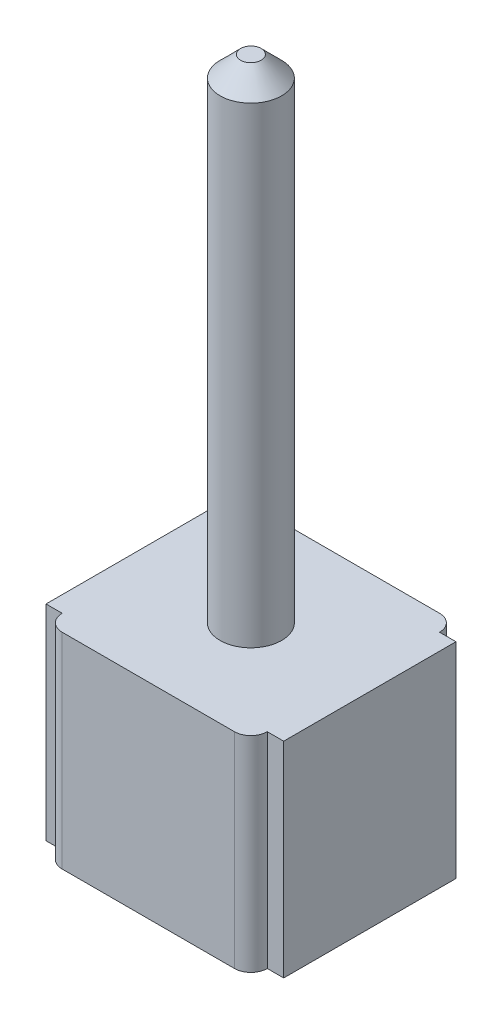
SolidWorks part; units mm, degrees
ref_plane "Plan de face" through (0, 0, 0) normal (0, 0, 1) x (1, 0, 0)
ref_plane "Plan de dessus" through (0, 0, 0) normal (0, 1, 0) x (1, 0, 0)
ref_plane "Plan de droite" through (0, 0, 0) normal (1, 0, 0) x (0, 0, -1)
sketch "Esquisse1" plane through (0, 0, 0) normal (0, 1, 0) x (1, 0, 0)
  line L0 (-1.25, 1.05) -> (-1.4469, 1.05)
  line L1 (-1.05, -1.25) -> (1.05, -1.25)
  line L3 (-1.05, 1.25) -> (1.05, 1.25)
  line L5 (-1.25, -1.25) -> (1.25, 1.25) construction
  line L6 (-1.25, 1.25) -> (1.25, -1.25) construction
  line L7 (-1.4469, 1.05) -> (-1.4469, -1.05)
  line L8 (-1.4469, -1.05) -> (-1.25, -1.05)
  line L10 (1.25, 1.05) -> (1.45, 1.05)
  line L11 (1.45, 1.05) -> (1.45, -1.05)
  line L12 (1.45, -1.05) -> (1.25, -1.05)
  arc A0 (-1.25, 1.05) -> (-1.05, 1.25) centre (-1.05, 1.05) cw
  arc A1 (-1.05, -1.25) -> (-1.25, -1.05) centre (-1.05, -1.05) cw
  arc A2 (1.05, -1.25) -> (1.25, -1.05) centre (1.05, -1.05) ccw
  arc A3 (1.05, 1.25) -> (1.25, 1.05) centre (1.05, 1.05) cw
  point P0 (0, 0)
  point P23 (0, 0)
  point P24 (0, 0)
  dimension "D3" = 0.2
  dimension "D1" = 2.5
  dimension "D2" = 2.5
extrude "Boss.-Extru.1" add sketch "Esquisse1" along normal blind 2.5
sketch "Esquisse3" plane through (0, 2.5, 0) normal (0, 1, 0) x (1, 0, 0)
  circle A0 centre (0, 0) radius 0.375
extrude "Boss.-Extru.2" add sketch "Esquisse3" along normal blind 6
chamfer "Chanfrein1" distance 0.25 angle 45 1 edges at (0, 8.5, 0.375)
sketch "Esquisse4" plane through (0, 0, 0) normal (0, -1, 0) x (1, 0, 0)
  line L1 (0, 0) -> (0.3042, 0)
  line L3 (0, -2.2509) -> (0.3042, -2.2509)
  line L4 (0.3042, 0) -> (0.3042, -2.2509)
  line L5 (0, 0) -> (-0.2993, 0)
  line L7 (0, -2.2509) -> (-0.2993, -2.2509)
  line L8 (-0.2993, 0) -> (-0.2993, -2.2509)
extrude "Boss.-Extru.3" add sketch "Esquisse4" along normal blind 0.2
fillet "Congé1" radius 0.15 1 edges at (0.0025, 0, -2.2509)
fillet "Congé2" radius 0.15 6 edges at (-0.2993, 0, -1.6755) (0.3042, 0, -1.6755) (0.3042, -0.0439, -2.207) (-0.2993, -0.0439, -2.207) (-0.2993, -0.175, -2.2509) (0.3042, -0.175, -2.2509)
